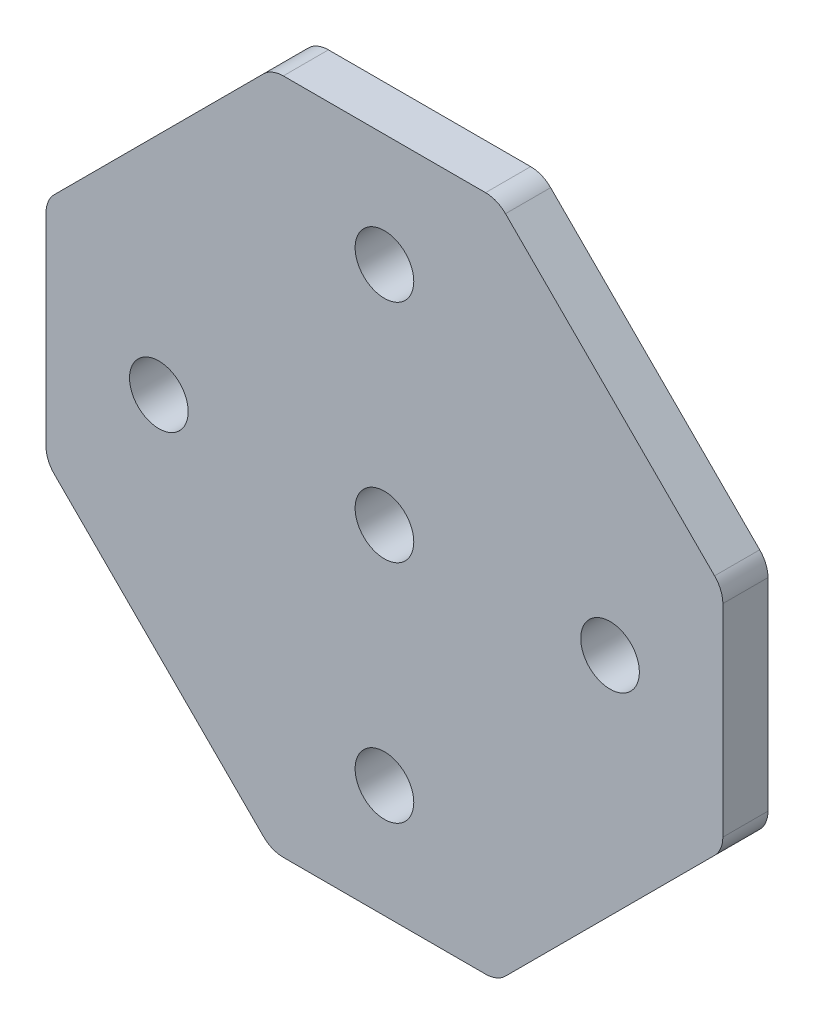
SolidWorks part; units mm, degrees
ref_plane "Спереди" through (0, 0, 0) normal (0, 0, 1) x (1, 0, 0)
ref_plane "Сверху" through (0, 0, 0) normal (0, 1, 0) x (1, 0, 0)
ref_plane "Справа" through (0, 0, 0) normal (1, 0, 0) x (0, 0, -1)
sketch "Эскиз1" plane through (0, 0, 0) normal (0, 0, 1) x (1, 0, 0)
  line L0 (0, 1.0355) -> (0, 18.9645)
  line L1 (0.7322, 20.7322) -> (19.2678, 39.2678)
  line L2 (21.0355, 40) -> (38.9645, 40)
  line L3 (40.7322, 39.2678) -> (59.2678, 20.7322)
  line L4 (60, 18.9645) -> (60, 1.0355)
  line L5 (59.2678, -0.7322) -> (40.7322, -19.2678)
  line L6 (38.9645, -20) -> (21.0355, -20)
  line L7 (19.2678, -19.2678) -> (0.7322, -0.7322)
  line L8 (10, 10) -> (30, 10) construction
  line L9 (30, 10) -> (30, 30) construction
  line L10 (30, 10) -> (30, -10) construction
  circle A0 centre (10, 10) radius 2.6
  circle A1 centre (30, 10) radius 2.6
  circle A2 centre (50, 10) radius 2.6
  circle A3 centre (30, 30) radius 2.6
  circle A4 centre (30, -10) radius 2.6
  arc A5 (0, 1.0355) -> (0.7322, -0.7322) centre (2.5, 1.0355) ccw
  arc A6 (21.0355, -20) -> (19.2678, -19.2678) centre (21.0355, -17.5) cw
  arc A7 (40.7322, -19.2678) -> (38.9645, -20) centre (38.9645, -17.5) cw
  arc A8 (60, 1.0355) -> (59.2678, -0.7322) centre (57.5, 1.0355) cw
  arc A9 (59.2678, 20.7322) -> (60, 18.9645) centre (57.5, 18.9645) cw
  arc A10 (38.9645, 40) -> (40.7322, 39.2678) centre (38.9645, 37.5) cw
  arc A11 (19.2678, 39.2678) -> (21.0355, 40) centre (21.0355, 37.5) cw
  arc A12 (0, 18.9645) -> (0.7322, 20.7322) centre (2.5, 18.9645) cw
  point P26 (0, 0)
  point P29 (20, -20)
  point P32 (40, -20)
  point P35 (60, 0)
  point P38 (60, 20)
  point P41 (40, 40)
  point P44 (20, 40)
  point P47 (0, 20)
  dimension "D7" = 5.2
  dimension "D16" = 2.5
  dimension "D1" = 20
  dimension "D2" = 20
  dimension "D3" = 20
  dimension "D4" = 20
  dimension "D5" = 20
  dimension "D6" = 20
  dimension "D8" = 10
  dimension "D9" = 10
  dimension "D11" = 20
  dimension "D13" = 20
  dimension "D15" = 20
  dimension "D10" = 3
  dimension "D12" = 2
  dimension "D14" = 2
extrude "Бобышка-Вытянуть1" add sketch "Эскиз1" along normal blind 4
